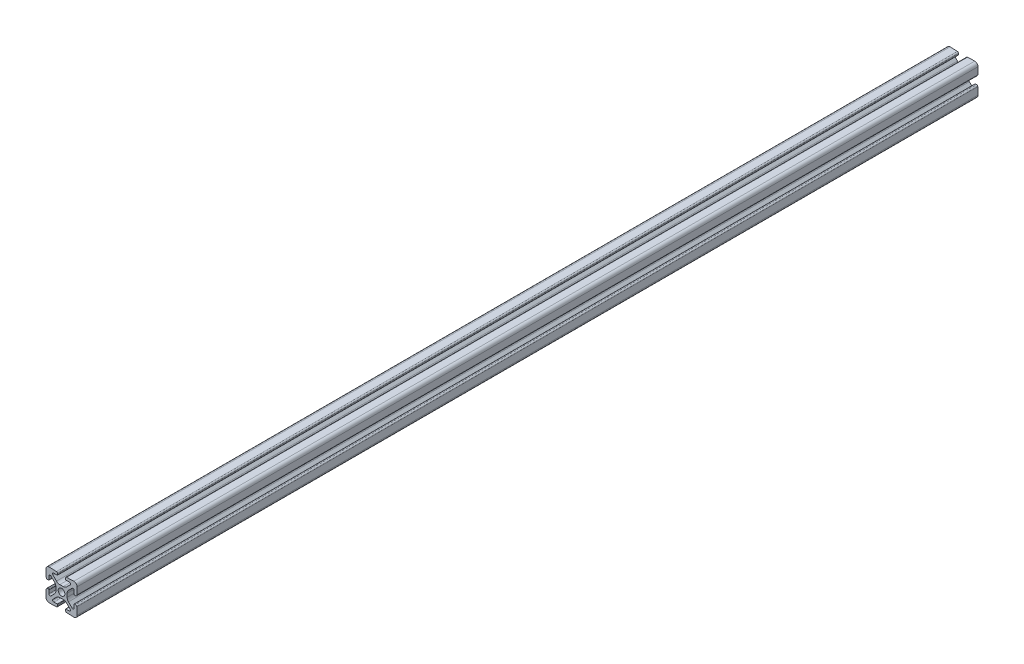
SolidWorks part; units mm, degrees
ref_plane "Front Plane" through (0, 0, 0) normal (0, 0, 1) x (1, 0, 0)
ref_plane "Top Plane" through (0, 0, 0) normal (0, 1, 0) x (1, 0, 0)
ref_plane "Right Plane" through (0, 0, 0) normal (1, 0, 0) x (0, 0, -1)
sketch "Sketch1" plane through (0, 0, 0) normal (0, 0, 1) x (1, 0, 0)
  line L0 (0, 0) -> (0, 10) construction
  line L1 (0, 0) -> (10, 0) construction
  line L2 (0, 0) -> (-10, 10) construction
  line L3 (-7.9302, 9.9988) -> (-3.2721, 9.8361)
  line L4 (-10, 10) -> (0, 10) construction
  line L6 (-2.8352, 8.0198) -> (-4.953, 8.0937)
  line L10 (0, 3.6) -> (-1.1022, 3.6)
  line L11 (-3.2236, 4.4787) -> (-5.5244, 6.7796)
  line L24 (0, 0) -> (-10, 0) construction
  line L25 (-10, 0) -> (0, 0) construction
  line L26 (0, 0) -> (0, -10) construction
  line L27 (-10, -10) -> (-10, 10) construction
  line L28 (0, 10) -> (10, 10) construction
  line L29 (-2.5249, 8.3091) -> (-2.5005, 9.0087)
  line L30 (-10, -10) -> (10, -10) construction
  arc A0 (-9.4142, 9.4142) -> (-7.9302, 9.9988) centre (-8, 8) cw
  arc A5 (-3.2721, 9.8361) -> (-2.5005, 9.0087) centre (-3.3, 9.0366) cw
  arc A6 (-1.1022, 3.6) -> (-3.2236, 4.4787) centre (-1.1022, 6.6) cw
  circle A16 centre (0, 0) radius 2.15
  arc A18 (-5.5244, 6.7796) -> (-4.953, 8.0937) centre (-4.9799, 7.3241) cw
  arc A20 (-2.8352, 8.0198) -> (-2.5249, 8.3091) centre (-2.8247, 8.3196) ccw
  point P15 (0, 0)
  point P42 (-2.3449, 3.6)
  point P80 (-10, 0)
  point P85 (0, -10)
  point P88 (0, -10)
  dimension "D11" = 2
  dimension "D15" = 3
  dimension "Center Hole Diameter" = 4.3
  dimension "D7" = 0.8
  dimension "D8" = 0.3
  dimension "D4" = 0.7701
  dimension "D1" = 45
  dimension "D2" = 2
  dimension "Rail Width" = 20
  dimension "T-Slot Depth" = 6.4
  dimension "D9" = 1.8
  dimension "Rail Height" = 20
  dimension "D23" = 7.2
  dimension "D5" = 11.5
  dimension "T-Slot Width" = 5
  dimension "D3" = 1.775
  dimension "D6" = 9.9598
sketch "Sketch2" plane through (0, 0, 0) normal (1, 0, 0) x (0, 0, -1)
  line L0 (-304.8, 0) -> (304.8, 0)
  line L1 (-304.8, -10) -> (-304.8, 10)
  line L2 (0, 0) -> (0, 10) construction
  line L3 (0, 0) -> (0, 10) construction
  line L4 (304.8, -10) -> (304.8, 10)
  point P0 (-274.8, 0)
  point P3 (0, 0)
  point P7 (274.8, 0)
  point P11 (-304.8, 0)
  point P14 (304.8, 0)
  dimension "D1" = 30
  dimension "Length" = 609.6
sketch "Sketch3" plane through (0, 0, 0) normal (0, 0, 1) x (1, 0, 0)
  line L0 (-2.5249, 8.3091) -> (-2.5005, 9.0087) construction
  line L1 (0, 0) -> (-10, 10) construction
  line L2 (0, 0) -> (-10, 10) construction
  line L5 (-7.9302, 9.9988) -> (-3.2721, 9.8361) construction
  line L6 (-2.8352, 8.0198) -> (-4.953, 8.0937) construction
  line L17 (-2.5249, 8.3091) -> (-2.5005, 9.0087)
  line L19 (-2.8352, 8.0198) -> (-4.953, 8.0937)
  line L20 (0, 0) -> (0, 10) construction
  line L21 (-3.6, 0) -> (-2.15, 0)
  line L22 (-3.6, 0) -> (-3.6, 1.1022)
  line L23 (-4.4787, 3.2236) -> (-6.7796, 5.5244)
  line L42 (-3.2236, 4.4787) -> (-5.5244, 6.7796) construction
  line L43 (0, 3.6) -> (-1.1022, 3.6) construction
  line L44 (-7.9302, 9.9988) -> (-3.2721, 9.8361)
  line L47 (-3.2236, 4.4787) -> (-5.5244, 6.7796)
  line L48 (0, 3.6) -> (-1.1022, 3.6)
  line L59 (0, 3.6) -> (0, 2.15)
  line L60 (-9.9988, 7.9302) -> (-9.8361, 3.2721)
  line L61 (-8.0198, 2.8352) -> (-8.0937, 4.953)
  line L62 (-8.3091, 2.5249) -> (-9.0087, 2.5005)
  arc A0 (-7.9302, 9.9988) -> (-9.4142, 9.4142) centre (-8, 8) ccw construction
  arc A1 (-2.8352, 8.0198) -> (-2.5249, 8.3091) centre (-2.8247, 8.3196) ccw construction
  arc A3 (-2.8352, 8.0198) -> (-2.5249, 8.3091) centre (-2.8247, 8.3196) ccw
  arc A5 (-7.9302, 9.9988) -> (-9.9988, 7.9302) centre (-8, 8) ccw
  circle A13 centre (0, 0) radius 2.15 construction
  arc A14 (0, 2.15) -> (-2.15, 0) centre (0, 0) ccw
  arc A15 (-4.4787, 3.2236) -> (-3.6, 1.1022) centre (-6.6, 1.1022) cw
  arc A16 (-8.0937, 4.953) -> (-6.7796, 5.5244) centre (-7.3241, 4.9799) cw
  arc A17 (-9.0087, 2.5005) -> (-9.8361, 3.2721) centre (-9.0366, 3.3) cw
  arc A18 (-8.0198, 2.8352) -> (-8.3091, 2.5249) centre (-8.3196, 2.8247) cw
  arc A36 (-2.5005, 9.0087) -> (-3.2721, 9.8361) centre (-3.3, 9.0366) ccw construction
  arc A38 (-4.953, 8.0937) -> (-5.5244, 6.7796) centre (-4.9799, 7.3241) ccw construction
  arc A39 (-3.2236, 4.4787) -> (-1.1022, 3.6) centre (-1.1022, 6.6) ccw construction
  arc A41 (-2.5005, 9.0087) -> (-3.2721, 9.8361) centre (-3.3, 9.0366) ccw
  arc A43 (-4.953, 8.0937) -> (-5.5244, 6.7796) centre (-4.9799, 7.3241) ccw
  arc A44 (-3.2236, 4.4787) -> (-1.1022, 3.6) centre (-1.1022, 6.6) ccw
extrude "Boss-Extrude1" add sketch "Sketch3" along normal mid plane 609.6
pattern_circular "CirPattern1" count 4 over 360 about axis through (0, 0, 0) along (0, 0, 1) of "Boss-Extrude1"
ref_plane "Contact Plane 1" through (0, 10, 0) normal (0, 1, 0) x (1, 0, 0)
ref_plane "Contact Plane 2" through (10, 0, 0) normal (1, 0, 0) x (0, 0, -1)
ref_plane "Contact Plane 3" through (0, -10, 0) normal (0, -1, 0) x (-1, 0, 0)
ref_plane "Contact Plane 4" through (-10, 0, 0) normal (-1, 0, 0) x (0, 0, 1)
sketch "Sketch4" plane through (0.3391, 9.71, 0) normal (0.0349, 0.9994, 0) x (0.9994, -0.0349, 0)
  line L0 (-10.3099, -275.2) -> (10.3067, -275.2)
  line L1 (10.3067, -275.2) -> (10.3067, -309.2762)
  line L2 (10.3067, -309.2762) -> (-10.3099, -309.2762)
  line L3 (-10.3099, -309.2762) -> (-10.3099, -275.2)
extrude "Cut-Extrude1" cut sketch "Sketch4" against normal through all both and the other way through all
equation "\"D1@Sketch2\"=\"Rail Width@Sketch1\"*1.5"
equation "\"D1@Boss-Extrude1\" = \"Length@Sketch2\""
